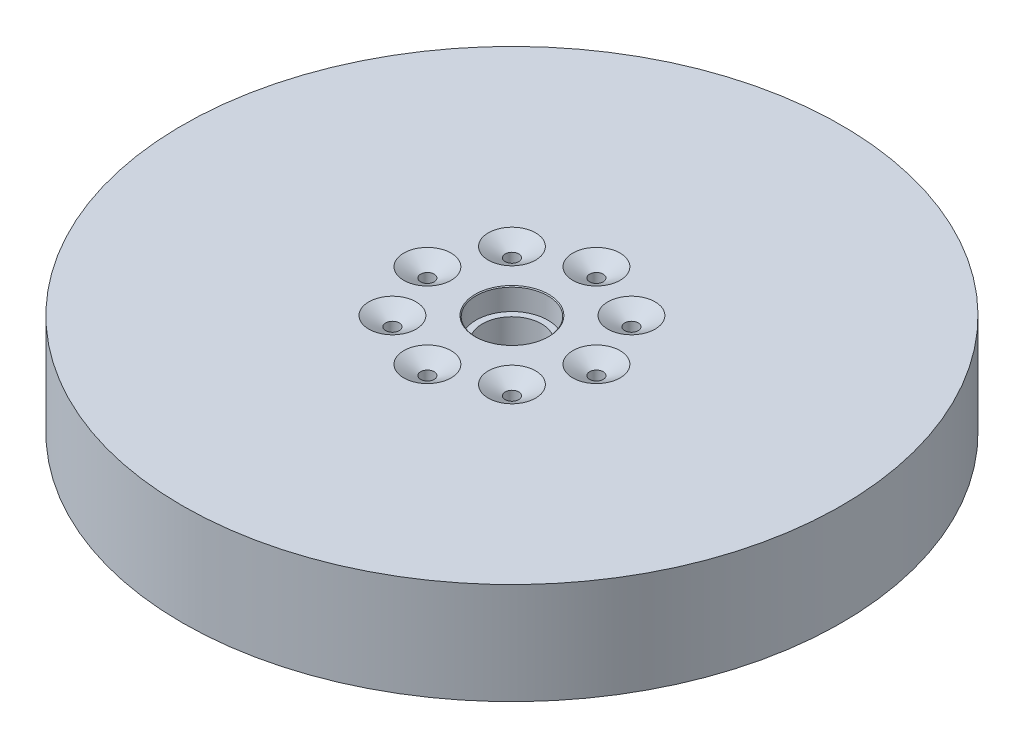
SolidWorks part; units mm, degrees
material "Ст 3 ГОСТ 380-88"
ref_plane "Front Plane" through (0, 0, 0) normal (0, 0, 1) x (1, 0, 0)
ref_plane "Top Plane" through (0, 0, 0) normal (0, 1, 0) x (1, 0, 0)
ref_plane "Right Plane" through (0, 0, 0) normal (1, 0, 0) x (0, 0, -1)
sketch "Sketch1" plane through (0, 0, 0) normal (1, 0, 0) x (0, 0, -1)
  line L0 (0, -14) -> (0, -31.7786) construction
  line L1 (-195, 60) -> (-195, 0)
  line L2 (-195, 0) -> (-185.5, 0)
  line L3 (-74.5, 0) -> (-74.5, -14)
  line L4 (-74.5, -14) -> (-20, -14)
  line L5 (-195, 60) -> (-185.5, 60)
  line L6 (0, 30.6711) -> (0, 60) construction
  line L7 (-17.5, 47) -> (-17.5, -11.5)
  line L8 (-17.5, -14) -> (0, -14) construction
  line L9 (0, 30.6711) -> (0, -14) construction
  line L10 (0, -14) -> (0, 30.6711) construction
  line L11 (-17.5, 60) -> (0, 60) construction
  line L12 (-20, 60) -> (-17.5, 57.5) construction
  line L13 (-20, -14) -> (-17.5, -11.5)
  line L14 (-21.25, 59.5) -> (-21.25, 47)
  line L15 (-21.25, 47) -> (-17.5, 47)
  line L16 (-21.25, 60) -> (-20, 60) construction
  line L17 (-17.5, 57.5) -> (-17.5, 47) construction
  line L18 (-21.75, 60) -> (-21.25, 59.5)
  line L19 (-185.5, 0) -> (-185.5, 10)
  line L20 (-185.5, 10) -> (-74.5, 10)
  line L21 (-74.5, 0) -> (-74.5, 10)
  line L22 (-185.5, 0) -> (-74.5, 0) construction
  line L23 (-185.5, 60) -> (-185.5, 50) construction
  line L24 (-185.5, 50) -> (-74.5, 50) construction
  line L25 (-74.5, 50) -> (-74.5, 60) construction
  line L26 (-185.5, 60) -> (-74.5, 60) construction
  line L27 (-74.5, 60) -> (-21.75, 60)
  line L28 (-185.5, 60) -> (-74.5, 60)
  dimension "D1" = 60
  dimension "D2" = 390
  dimension "D3" = 149
  dimension "D4" = 14
  dimension "D5" = 17.5
  dimension "D6" = 13
  dimension "D7" = 42.5
  dimension "D10" = 10
  dimension "D11" = 9.5
  dimension "D13" = 10
revolve "Revolve1" add sketch "Sketch1" angle 360 about L0
sketch "Sketch2" plane through (0, 60, 0) normal (0, 1, 0) x (1, 0, 0)
  line L0 (-50, 0) -> (0, 0) construction
  circle A0 centre (-50, 0) radius 4
  circle A1 centre (-35.3553, 35.3553) radius 4
  circle A2 centre (0, 50) radius 4
  circle A3 centre (35.3553, 35.3553) radius 4
  circle A4 centre (50, 0) radius 4
  circle A5 centre (35.3553, -35.3553) radius 4
  circle A6 centre (0, -50) radius 4
  circle A7 centre (-35.3553, -35.3553) radius 4
  point P21 (0, 0)
  dimension "D1" = 8
  dimension "D2" = 8
  dimension "D3" = 50
extrude "Cut-Extrude1" cut sketch "Sketch2" against normal through all both and the other way through all
sketch "Sketch3" plane through (0, 10, 0) normal (0, -1, 0) x (1, 0, 0)
  line L0 (0, 129.2853) -> (0, -136.9499) construction
  line L1 (0, 0) -> (0, 132.1781) construction
  line L2 (0, 0) -> (-104.479, 104.479) construction
  circle A0 centre (0, 82) radius 2
  circle A1 centre (0, 120) radius 2
  circle A2 centre (84.8528, 84.8528) radius 2
  circle A3 centre (57.9828, 57.9828) radius 2 construction
  circle A4 centre (120, 0) radius 2
  circle A5 centre (82, 0) radius 2
  circle A6 centre (84.8528, -84.8528) radius 2
  circle A7 centre (57.9828, -57.9828) radius 2 construction
  circle A8 centre (0, -120) radius 2
  circle A9 centre (0, -82) radius 2
  circle A10 centre (-84.8528, -84.8528) radius 2
  circle A11 centre (-57.9828, -57.9828) radius 2 construction
  circle A12 centre (-120, 0) radius 2
  circle A13 centre (-82, 0) radius 2
  circle A14 centre (-84.8528, 84.8528) radius 2
  circle A15 centre (-57.9828, 57.9828) radius 2 construction
  circle A16 centre (0, 0) radius 120 construction
  point P104 (0, 0)
  dimension "D1" = 4
  dimension "D4" = 120
  dimension "D3" = 240
  dimension "D2" = 82
  dimension "D6" = 45
  dimension "D5" = 8
extrude "Cut-Extrude2" [suppressed] cut sketch "Sketch3" against normal blind 15
ref_plane "Plane1" through (0, 30, 0) normal (0, -1, 0) x (-1, 0, 0)
mirror "Mirror1" [suppressed] about plane through (0, 30, 0) normal (0, -1, 0)
sketch "Sketch4" plane through (0, 60, 0) normal (0, 1, 0) x (1, 0, 0)
  circle A0 centre (0, 50) radius 8
  circle A1 centre (0, 0) radius 50 construction
  circle A2 centre (35.3553, 35.3553) radius 8
  circle A3 centre (50, 0) radius 8
  circle A4 centre (35.3553, -35.3553) radius 8
  circle A5 centre (0, -50) radius 8
  circle A6 centre (-35.3553, -35.3553) radius 8
  circle A7 centre (-50, 0) radius 8
  circle A8 centre (-35.3553, 35.3553) radius 8
  point P22 (0, 0)
  dimension "D1" = 16
  dimension "D2" = 8
extrude "Cut-Extrude3" [suppressed] cut sketch "Sketch4" against normal blind 12
sketch "Sketch5" plane through (0, -14, 0) normal (0, -1, 0) x (1, 0, 0)
  circle A0 centre (35.3553, -35.3553) radius 4 construction
  circle A1 centre (0, 0) radius 74.5
  circle A2 centre (0, 0) radius 74.5
  circle A3 centre (0, -50) radius 4 construction
  circle A4 centre (-35.3553, -35.3553) radius 4 construction
  circle A5 centre (-50, 0) radius 4 construction
  circle A6 centre (50, 0) radius 4 construction
  circle A7 centre (35.3553, 35.3553) radius 4 construction
  circle A8 centre (-35.3553, 35.3553) radius 4 construction
  circle A9 centre (0, 50) radius 4 construction
  circle A10 centre (35.3553, -35.3553) radius 4
  circle A11 centre (0, -50) radius 4
  circle A12 centre (-35.3553, -35.3553) radius 4
  circle A13 centre (-50, 0) radius 4
  circle A14 centre (50, 0) radius 4
  circle A15 centre (35.3553, 35.3553) radius 4
  circle A16 centre (-35.3553, 35.3553) radius 4
  circle A17 centre (0, 50) radius 4
  circle A18 centre (0, 0) radius 17.5 construction
  circle A19 centre (0, 0) radius 17.5
  dimension "D1" = 0
extrude "Boss-Extrude1" add sketch "Sketch5" along normal blind 1 from offset 30 separate body
sketch "Sketch6" plane through (0, -14, 0) normal (0, -1, 0) x (1, 0, 0)
  circle A1 centre (0, 0) radius 74.5
  circle A2 centre (0, 0) radius 74.5
  dimension "D1" = 0
extrude "Cut-Extrude4" cut sketch "Sketch6" against normal blind 2.5
chamfer "Chamfer1" distance 5 angle 60 8 edges at (-50, -11.5, -4) (-35.3553, -11.5, -39.3553) (0, -11.5, -54) (35.3553, -11.5, -39.3553) (50, -11.5, -4) (35.3553, -11.5, 31.3553) (-35.3553, -11.5, 31.3553) (0, -11.5, 46)
chamfer "Chamfer2" distance 10 angle 30 8 edges at (-50, 60, 4) (-35.3553, 60, -31.3553) (0, 60, -46) (35.3553, 60, -31.3553) (50, 60, 4) (35.3553, 60, 39.3553) (0, 60, 54) (-35.3553, 60, 39.3553)
sketch "Sketch7" plane through (0, 10, 0) normal (0, -1, 0) x (1, 0, 0)
  line L0 (0, 234.4435) -> (0, -294.1465) construction
  line L1 (0, 0) -> (14.3697, 72.2412) construction
  line L3 (-14.3697, 72.2412) -> (-35.6345, 179.1468) construction
  line L4 (14.1411, 73.6548) -> (35.4061, 180.5614)
  line L5 (-14.1411, 73.6548) -> (-35.4061, 180.5614)
  line L6 (14.3697, 72.2412) -> (35.6345, 179.1468) construction
  line L7 (36.1893, 181.9357) -> (45.8571, 230.5392) construction
  line L8 (35.6345, 179.1468) -> (36.1893, 181.9357) construction
  line L9 (0, 75) -> (22.6048, 75) construction
  line L10 (0, 129.5) -> (22.6048, 129.5) construction
  line L11 (0, 184) -> (132.4756, 184) construction
  circle A1 centre (0, 0) radius 17.5 construction
  arc A2 (35.4061, 180.5614) -> (-35.4061, 180.5614) centre (0, 0) ccw
  circle A3 centre (0, 157) radius 2.6
  circle A4 centre (0, 0) radius 185.5 construction
  circle A6 centre (0, 102) radius 2.6
  arc A8 (-35.144, 179.2437) -> (-35.6345, 179.1468) centre (0, 0) ccw construction
  arc A9 (14.1411, 73.6548) -> (-14.1411, 73.6548) centre (0, 0) ccw
  dimension "D1" = 11.25
  dimension "D2" = 184
  dimension "D3" = 371
  dimension "D5" = 0.5
  dimension "D6" = 75
  dimension "D7" = 5.2
  dimension "D4" = 109
  dimension "D8" = 54.5
  dimension "D9" = 55
extrude "Boss-Extrude3" add sketch "Sketch7" along normal blind 5 from offset 0.01 separate body
sketch "Sketch8" plane through (0, 4.99, 0) normal (0, -1, 0) x (1, 0, 0)
  line L2 (14.1411, 73.6548) -> (35.4061, 180.5614)
  line L3 (-35.4061, 180.5614) -> (-14.1411, 73.6548)
  line L4 (14.1411, 73.6548) -> (35.4061, 180.5614)
  line L5 (-35.4061, 180.5614) -> (-14.1411, 73.6548)
  circle A0 centre (0, 102) radius 2.6 construction
  circle A1 centre (0, 157) radius 2.6 construction
  arc A2 (14.1411, 73.6548) -> (-14.1411, 73.6548) centre (0, 0) ccw
  arc A3 (35.4061, 180.5614) -> (-35.4061, 180.5614) centre (0, 0) ccw
  arc A4 (14.1411, 73.6548) -> (-14.1411, 73.6548) centre (0, 0) ccw
  arc A5 (35.4061, 180.5614) -> (-35.4061, 180.5614) centre (0, 0) ccw
  circle A6 centre (0, 102) radius 2.6
  circle A7 centre (0, 157) radius 2.6
  dimension "D1" = 0
extrude "Boss-Extrude4" add sketch "Sketch8" along normal blind 5 separate body
chamfer "Chamfer3" distance 3.5 angle 45 2 edges at (0, -0.01, 99.4) (0, -0.01, 154.4)
chamfer "Chamfer4" distance 3.5 angle 45 2 edges at (0, 9.99, 104.6) (0, 9.99, 154.4)
sketch "Sketch9" plane through (0, 10, 0) normal (0, -1, 0) x (1, 0, 0)
  line L0 (0, 0) -> (0, 213.1478) construction
  circle A0 centre (0, 157) radius 2.6
  circle A1 centre (0, 157) radius 2.6 construction
  circle A2 centre (0, -157) radius 2.6
  circle A3 centre (0, 102) radius 2.6
  circle A4 centre (0, 102) radius 2.6 construction
  circle A5 centre (60.0813, 145.0491) radius 2.6
  circle A6 centre (39.0337, 94.2357) radius 2.6
  circle A7 centre (111.0158, 111.0158) radius 2.6
  circle A8 centre (72.1249, 72.1249) radius 2.6
  circle A9 centre (145.0491, 60.0813) radius 2.6
  circle A10 centre (94.2357, 39.0337) radius 2.6
  circle A11 centre (157, 0) radius 2.6
  circle A12 centre (102, 0) radius 2.6
  circle A13 centre (145.0491, -60.0813) radius 2.6
  circle A14 centre (94.2357, -39.0337) radius 2.6
  circle A15 centre (111.0158, -111.0158) radius 2.6
  circle A16 centre (72.1249, -72.1249) radius 2.6
  circle A17 centre (60.0813, -145.0491) radius 2.6
  circle A18 centre (39.0337, -94.2357) radius 2.6
  circle A19 centre (0, -102) radius 2.6
  circle A20 centre (-60.0813, -145.0491) radius 2.6
  circle A21 centre (-39.0337, -94.2357) radius 2.6
  circle A22 centre (-111.0158, -111.0158) radius 2.6
  circle A23 centre (-72.1249, -72.1249) radius 2.6
  circle A24 centre (-145.0491, -60.0813) radius 2.6
  circle A25 centre (-94.2357, -39.0337) radius 2.6
  circle A26 centre (-157, 0) radius 2.6
  circle A27 centre (-102, 0) radius 2.6
  circle A28 centre (-145.0491, 60.0813) radius 2.6
  circle A29 centre (-94.2357, 39.0337) radius 2.6
  circle A30 centre (-111.0158, 111.0158) radius 2.6
  circle A31 centre (-72.1249, 72.1249) radius 2.6
  circle A32 centre (-60.0813, 145.0491) radius 2.6
  circle A33 centre (-39.0337, 94.2357) radius 2.6
  point P42 (0, 0)
  dimension "D1" = 5.2
  dimension "D2" = 16
extrude "Cut-Extrude5" cut sketch "Sketch9" against normal blind 15
sketch "Sketch10" plane through (0, -0.01, 0) normal (0, -1, 0) x (1, 0, 0)
  line L0 (-30.5248, 78.0837) -> (15.022, 78.0837)
  line L1 (14.1411, 73.6548) -> (35.4061, 180.5614) construction
  line L2 (15.022, 78.0837) -> (14.1411, 73.6548)
  line L3 (14.1411, 73.6548) -> (-14.1411, 73.6548)
  line L4 (-14.1411, 73.6548) -> (-30.5248, 78.0837)
  point P3 (-7.7514, 78.0837)
extrude "Cut-Extrude6" cut sketch "Sketch10" against normal blind 10
pattern_circular "CirPattern5" count 4 over 360 about axis through (0, 0, 0) along (0, 1, 0) of bodies 119 120
sketch "Sketch11" plane through (0, 10, 0) normal (0, -1, 0) x (1, 0, 0)
  line L0 (0, 216.07) -> (0, 0) construction
  line L1 (0, 0) -> (38.0387, 91.8336) construction
  line L2 (15.8518, 77.9512) -> (36.2297, 180.3979)
  line L3 (56.3854, 84.9981) -> (86.9419, 130.7291) construction
  line L4 (15.8518, 77.9512) -> (29.8813, 72.1399)
  line L5 (15.022, 78.0837) -> (-15.022, 78.0837) construction
  line L6 (15.022, 78.0837) -> (35.4061, 180.5614) construction
  line L7 (70.4138, 169.9938) -> (61.0763, 147.4512)
  line L8 (29.8813, 72.1399) -> (43.9109, 66.3287) construction
  line L9 (43.9109, 66.3287) -> (56.3854, 84.9981) construction
  line L10 (86.9419, 130.7291) -> (101.9423, 153.1789) construction
  line L11 (59.0863, 142.647) -> (60.0813, 145.0491) construction
  line L12 (61.0763, 147.4512) -> (91.559, 221.0429) construction
  line L13 (60.0813, 145.0491) -> (59.0863, 142.647) construction
  line L14 (59.0863, 142.647) -> (40.0287, 96.6378)
  line L15 (60.0813, 145.0491) -> (61.0763, 147.4512) construction
  line L16 (61.0763, 147.4512) -> (60.0813, 145.0491) construction
  line L17 (38.0387, 91.8336) -> (39.0337, 94.2357) construction
  line L18 (40.0287, 96.6378) -> (59.0863, 142.647) construction
  line L19 (39.0337, 94.2357) -> (38.0387, 91.8336) construction
  line L20 (38.0387, 91.8336) -> (29.8813, 72.1399)
  line L21 (40.0287, 96.6378) -> (39.0337, 94.2357) construction
  line L22 (39.0337, 94.2357) -> (40.0287, 96.6378) construction
  arc A0 (36.6191, 95.2) -> (39.0337, 94.2357) centre (0, 0) ccw construction
  arc A1 (57.6711, 146.0241) -> (62.4751, 144.0343) centre (0, 0) ccw construction
  arc A2 (29.8813, 72.1399) -> (0, 78.0837) centre (0, 0) ccw construction
  arc A3 (36.2297, 180.3979) -> (70.4138, 169.9938) centre (0, 0) cw
  arc A4 (38.0387, 91.8336) -> (41.4229, 93.2102) centre (39.0337, 94.2357) ccw construction
  circle A5 centre (0, 0) radius 185.5 construction
  arc A6 (39.0337, 94.2357) -> (36.6191, 95.2) centre (0, 0) ccw construction
  arc A7 (0, 78.0837) -> (29.8813, 72.1399) centre (0, 0) ccw construction
  arc A8 (70.4138, 169.9938) -> (101.9423, 153.1789) centre (0, 0) cw construction
  arc A9 (61.0763, 147.4512) -> (59.0863, 142.647) centre (60.0813, 145.0491) ccw
  arc A10 (60.0813, 145.0491) -> (57.6711, 146.0241) centre (0, 0) ccw construction
  arc A11 (59.0863, 142.647) -> (62.4751, 144.0343) centre (60.0813, 145.0491) ccw construction
  arc A12 (62.4751, 144.0343) -> (60.0813, 145.0491) centre (0, 0) ccw construction
  arc A13 (62.4751, 144.0343) -> (61.0763, 147.4512) centre (60.0813, 145.0491) ccw construction
  arc A14 (40.0287, 96.6378) -> (38.0387, 91.8336) centre (39.0337, 94.2357) ccw
  arc A15 (41.4229, 93.2102) -> (40.0287, 96.6378) centre (39.0337, 94.2357) ccw construction
  dimension "D1" = 22.5
  dimension "D3" = 0.8397
  dimension "D4" = 184
  dimension "D5" = 5.2
  dimension "D2" = 22.5
extrude "Boss-Extrude5" add sketch "Sketch11" along normal blind 10 from offset 0.01 separate body
chamfer "Chamfer5" distance 3.5 angle 45 2 edges at (36.6316, -0.01, 95.2307) (57.6792, -0.01, 146.0441)
chamfer "Chamfer6" distance 3.5 angle 45 2 edges at (36.6316, 9.99, 95.2307) (57.6792, 9.99, 146.0441)
